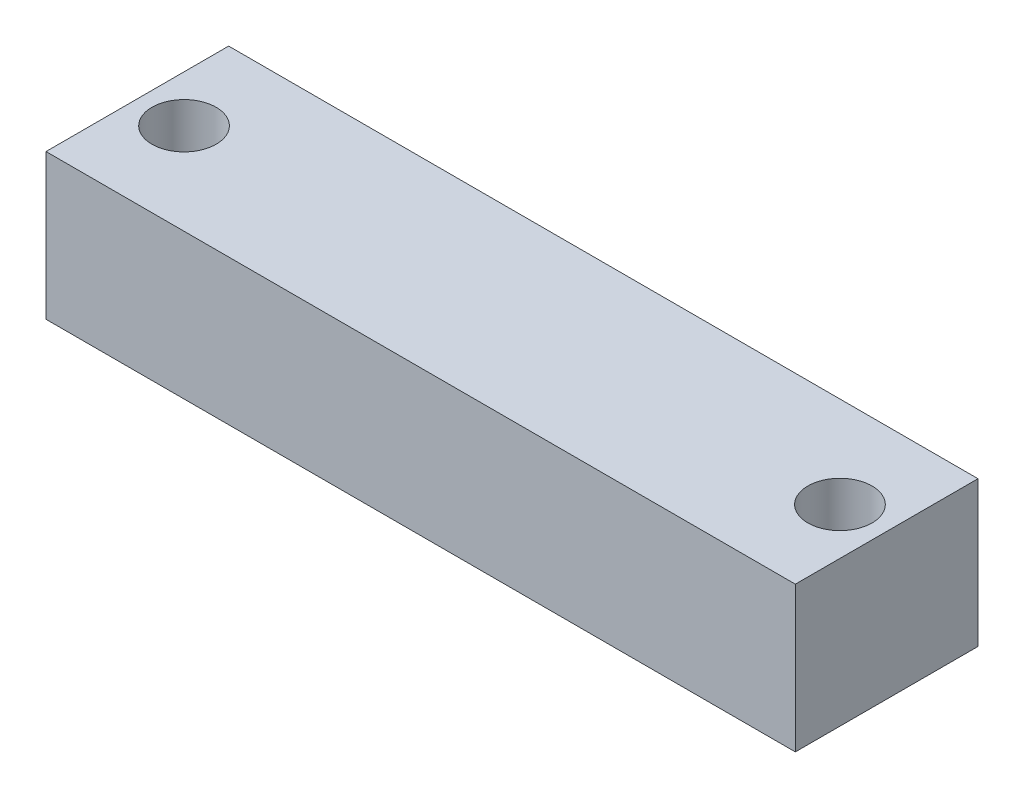
SolidWorks part; units mm, degrees
ref_plane "Front Plane" through (0, 0, 0) normal (0, 0, 1) x (1, 0, 0)
ref_plane "Top Plane" through (0, 0, 0) normal (0, 1, 0) x (1, 0, 0)
ref_plane "Right Plane" through (0, 0, 0) normal (1, 0, 0) x (0, 0, -1)
sketch "Sketch1" plane through (0, 0, 0) normal (0, 1, 0) x (1, 0, 0)
  line L1 (-45.125, -11) -> (45.125, -11)
  line L2 (-45.125, -11) -> (-45.125, 11)
  line L3 (-45.125, 11) -> (45.125, 11)
  line L4 (45.125, -11) -> (45.125, 11)
  line L5 (-45.125, -11) -> (45.125, 11) construction
  line L6 (-45.125, 11) -> (45.125, -11) construction
  point P0 (0, 0)
  dimension "D1" = 90.25
  dimension "D2" = 22
extrude "Boss-Extrude1" add sketch "Sketch1" along normal blind 17.5
sketch "Sketch2" plane through (0, 17.5, 0) normal (0, 1, 0) x (1, 0, 0)
  line L0 (0, 11) -> (0, -11) construction
  line L1 (45.125, 11) -> (-45.125, 11) construction
  line L2 (-45.125, -11) -> (45.125, -11) construction
  line L3 (-45.125, 0) -> (45.125, 0) construction
  line L4 (-45.125, 11) -> (-45.125, -11) construction
  line L5 (45.125, -11) -> (45.125, 11) construction
  circle A0 centre (-39.5, 0) radius 1.5
  circle A1 centre (39.5, 0) radius 1.5
  point P10 (0, 0)
  point P17 (0, 0)
  point P18 (0, 0)
  point P19 (0, 0)
  dimension "D2" = 3
  dimension "D1" = 79
extrude "Cut-Extrude1" cut sketch "Sketch2" against normal through all and the other way through all
sketch "Sketch3" plane through (0, 17.5, 0) normal (0, 1, 0) x (1, 0, 0)
  line L1 (-43.365, 11) -> (-43.365, -11)
  line L2 (-45.125, 11) -> (-45.125, -11) construction
  line L3 (45.125, 11) -> (-45.125, 11) construction
  line L4 (-45.125, -11) -> (45.125, -11) construction
  circle A0 centre (-39.5, 0) radius 3.865
  circle A1 centre (39.5, 0) radius 3.865
  point P10 (0, 0)
  point P11 (0, 0)
  point P14 (0, 0)
  circle M2 centre (-39.5, 0) radius 1.5
  circle M3 centre (39.5, 0) radius 1.5
  dimension "D1" = 1.76
extrude "Cut-Extrude2" cut sketch "Sketch3" against normal blind 10 contours A0 M2 | A1 M3
